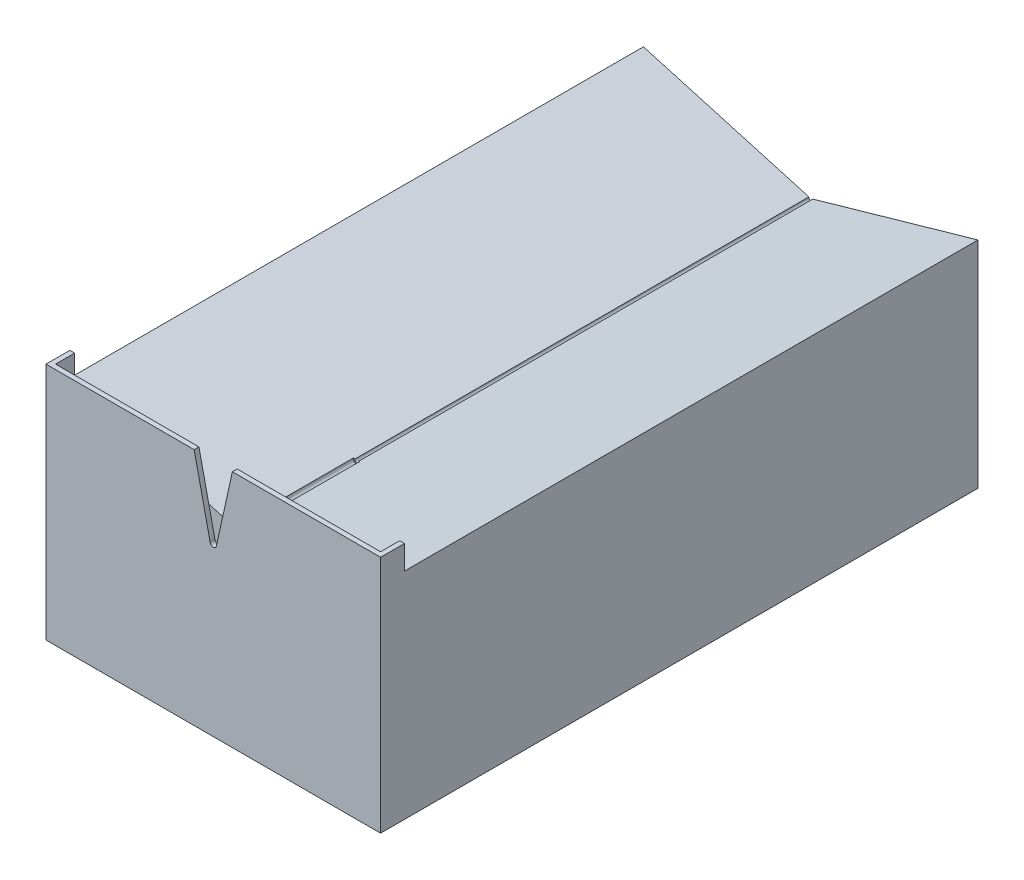
SolidWorks part; units mm, degrees
ref_plane "Plano frontal" through (0, 0, 0) normal (0, 0, 1) x (1, 0, 0)
ref_plane "Plano superior" through (0, 0, 0) normal (0, 1, 0) x (1, 0, 0)
ref_plane "Plano direito" through (0, 0, 0) normal (1, 0, 0) x (0, 0, -1)
sketch "Esboço1" plane through (0, 0, 0) normal (0, 0, 1) x (1, 0, 0)
  line L1 (35, -22.5) -> (-35, -22.5)
  line L2 (35, -22.5) -> (35, 22.5)
  line L4 (-35, -22.5) -> (-35, 22.5)
  line L5 (35, -22.5) -> (-35, 22.5) construction
  line L6 (35, 22.5) -> (-35, -22.5) construction
  line L7 (-35, 22.5) -> (-0.3846, 12.6099)
  line L8 (0.4289, 12.6225) -> (35, 22.5)
  arc A0 (-0.3846, 12.6099) -> (0.4289, 12.6225) centre (0.024, 12.4931) ccw
  point P0 (0, 0)
  dimension "D3" = 0.85
  dimension "D1" = 45
  dimension "D2" = 70
extrude "Ressalto-extrusão2" add sketch "Esboço1" along normal blind 120
sketch "Esboço2" plane through (0, 0, 120) normal (0, 0, 1) x (1, 0, 0)
  line L0 (-35, -22.5) -> (35, -22.5)
  line L1 (-35, -22.5) -> (-35, 27.5)
  line L2 (35, -22.5) -> (35, 27.5)
  line L3 (-35, 27.5) -> (35, 27.5)
  dimension "D1" = 50
extrude "Ressalto-extrusão3" add sketch "Esboço2" along normal blind 5
sketch "Esboço3" plane through (0, 27.5, 0) normal (0, 1, 0) x (1, 0, 0)
  line L5 (35, -124) -> (-35, -124)
  line L6 (34, -124) -> (-34, -124)
  line L8 (-34, -125) -> (-34, -120)
  line L9 (-34, -124) -> (-34, -120)
  line L10 (-34, -120) -> (34, -120)
  line L11 (34, -125) -> (34, -120)
  line L12 (34, -124) -> (34, -120)
  dimension "D1" = 1
  dimension "D2" = 1
  dimension "D3" = 1
extrude "Corte-extrusão1" cut sketch "Esboço3" against normal blind 48
sketch "Esboço5" plane through (0, 0, 0) normal (0, 0, -1) x (-1, 0, 0)
  circle A0 centre (0, 12.5) radius 0.4
extrude "Corte-extrusão4" cut sketch "Esboço5" against normal blind 127
sketch "Esboço6" plane through (0, 0, 125) normal (0, 0, 1) x (1, 0, 0)
  circle A0 centre (0, 12.5) radius 0.675
  dimension "D1" = 1.35
extrude "Corte-extrusão6" cut sketch "Esboço6" against normal blind 30
sketch "Esboço7" plane through (0, 0, 125) normal (0, 0, 1) x (1, 0, 0)
  line L0 (0.675, 12.5) -> (4, 27.5)
  line L1 (35, 27.5) -> (-35, 27.5) construction
  line L2 (4, 27.5) -> (0, 27.5)
  line L3 (0, 27.5) -> (-4, 27.5)
  line L4 (-0.675, 12.5) -> (-4, 27.5)
  line L5 (-0.675, 12.5) -> (0.675, 12.5)
  circle A0 centre (0, 12.5) radius 0.675 construction
extrude "Corte-extrusão7" cut sketch "Esboço7" against normal blind 4
